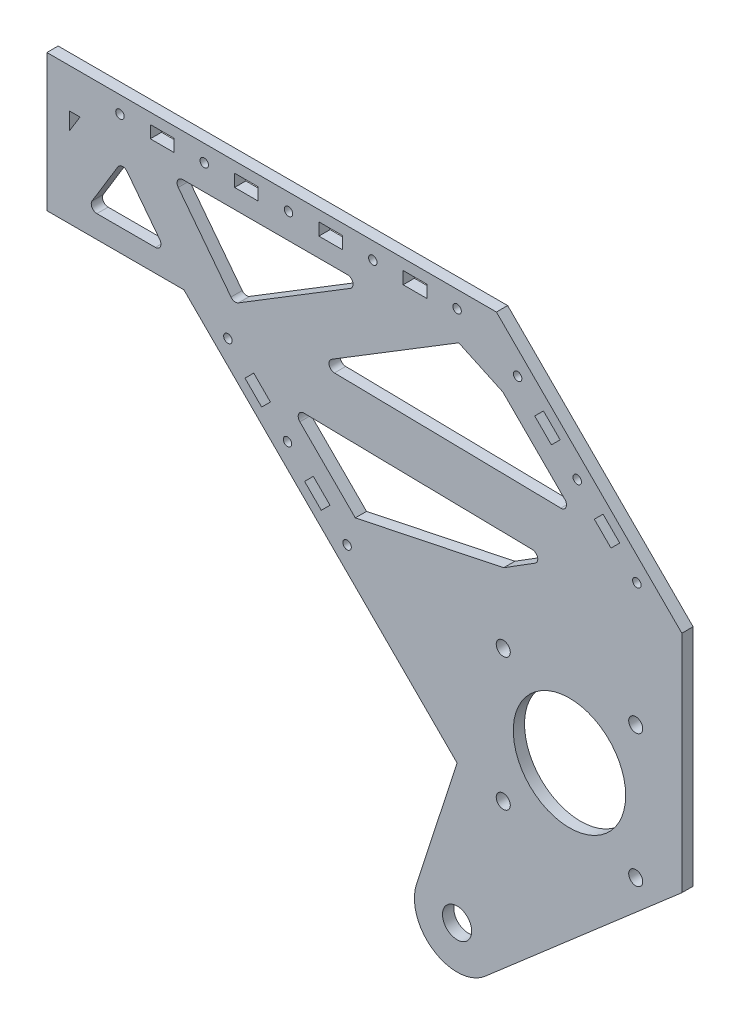
SolidWorks part; units mm, degrees
ref_plane "前视基准面" through (0, 0, 0) normal (0, 0, 1) x (1, 0, 0)
ref_plane "上视基准面" through (0, 0, 0) normal (0, 1, 0) x (1, 0, 0)
ref_plane "右视基准面" through (0, 0, 0) normal (1, 0, 0) x (0, 0, -1)
sketch "草图1" plane through (0, 0, 0) normal (0, 0, 1) x (1, 0, 0)
  line L261 (47.0274, 35.0547) -> (47.0274, 15.0547) construction
  line L316 (-52.9726, 135.0547) -> (-52.9726, 126.7057) construction
  line L332 (-112.9726, 135.0547) -> (-97.9726, 135.0547) construction
  line L334 (-42.1726, 137.2547) -> (-33.7726, 137.2547)
  line L335 (-42.1726, 137.2547) -> (-42.1726, 132.8547)
  line L336 (-42.1726, 132.8547) -> (-33.7726, 132.8547)
  line L337 (-33.7726, 137.2547) -> (-33.7726, 132.8547)
  line L338 (-42.1726, 137.2547) -> (-33.7726, 132.8547) construction
  line L339 (-42.1726, 132.8547) -> (-33.7726, 137.2547) construction
  line L389 (-138.9726, 141.0547) -> (21.0274, 141.0547)
  line L390 (-22.9726, 135.0547) -> (-22.9726, 144.5851) construction
  line L395 (-37.9726, 135.0547) -> (-7.9726, 135.0547) construction
  line L418 (87.0274, 75.0547) -> (21.0274, 141.0547)
  line L419 (-3.7726, 132.8547) -> (-12.1726, 137.2547) construction
  line L420 (-3.7726, 137.2547) -> (-12.1726, 132.8547) construction
  line L421 (7.0274, 135.0547) -> (-7.9726, 135.0547) construction
  line L422 (-12.1726, 137.2547) -> (-12.1726, 132.8547)
  line L423 (-3.7726, 132.8547) -> (-12.1726, 132.8547)
  line L424 (-3.7726, 137.2547) -> (-3.7726, 132.8547)
  line L443 (-3.7726, 137.2547) -> (-12.1726, 137.2547)
  line L444 (-102.1726, 137.2547) -> (-93.7726, 132.8547) construction
  line L445 (-102.1726, 132.8547) -> (-93.7726, 137.2547) construction
  line L446 (7.0274, -4.9453) -> (-138.9726, 141.0547) construction
  line L447 (-67.9726, 135.0547) -> (-97.9726, 135.0547) construction
  line L448 (47.0274, 15.0547) -> (7.0274, -54.2273) construction
  line L449 (-63.7726, 132.8547) -> (-72.1726, 137.2547) construction
  line L483 (-63.7726, 137.2547) -> (-72.1726, 132.8547) construction
  line L515 (47.0274, 35.0547) -> (47.0274, 135.0547) construction
  line L516 (47.0274, 135.0547) -> (-52.9726, 135.0547) construction
  line L517 (-102.1726, 137.2547) -> (-93.7726, 137.2547)
  line L518 (-102.1726, 137.2547) -> (-102.1726, 132.8547)
  line L519 (-102.1726, 132.8547) -> (-93.7726, 132.8547)
  line L520 (-93.7726, 137.2547) -> (-93.7726, 132.8547)
  line L521 (-72.1726, 137.2547) -> (-72.1726, 132.8547)
  line L522 (-63.7726, 132.8547) -> (-72.1726, 132.8547)
  line L523 (-63.7726, 137.2547) -> (-63.7726, 132.8547)
  line L524 (-63.7726, 137.2547) -> (-72.1726, 137.2547)
  line L525 (7.0274, -4.9453) -> (-7.4315, -49.5392)
  line L551 (7.0274, -4.9453) -> (87.0274, -4.9453) construction
  line L552 (7.0274, -4.9453) -> (7.0274, 75.0547) construction
  line L553 (7.0274, 75.0547) -> (87.0274, 75.0547) construction
  line L554 (87.0274, -4.9453) -> (87.0274, 75.0547)
  line L555 (87.0274, -4.9453) -> (16.9882, -65.7087)
  line L556 (21.4033, 132.1936) -> (81.3921, 72.2048) construction
  line L557 (54.0274, 108.0547) -> (35.0674, 89.0947) construction
  line L558 (43.7037, 113.0045) -> (34.6527, 115.8329) construction
  line L559 (55.8659, 94.6197) -> (61.8056, 88.68)
  line L576 (55.8659, 94.6197) -> (58.9772, 97.731)
  line L577 (58.9772, 97.731) -> (64.9169, 91.7913)
  line L578 (61.8056, 88.68) -> (64.9169, 91.7913)
  line L579 (55.8659, 94.6197) -> (64.9169, 91.7913) construction
  line L580 (58.9772, 97.731) -> (61.8056, 88.68) construction
  line L581 (40.5924, 109.8932) -> (37.764, 118.9442) construction
  line L582 (34.6527, 115.8329) -> (37.764, 118.9442)
  line L583 (43.7037, 113.0045) -> (37.764, 118.9442)
  line L584 (40.5924, 109.8932) -> (43.7037, 113.0045)
  line L585 (40.5924, 109.8932) -> (34.6527, 115.8329)
  line L586 (60.3914, 93.2055) -> (58.8358, 91.6499) construction
  line L587 (39.1782, 114.4187) -> (37.6226, 112.8631) construction
  line L588 (-138.9726, 141.0547) -> (-138.9726, 92.2861)
  line L589 (14.0274, 68.0547) -> (9.4285, 72.6537) construction
  line L605 (-25.9726, 28.0547) -> (-21.7299, 32.2974) construction
  line L606 (-138.9726, 92.2861) -> (-90.2039, 92.2861)
  line L607 (-81.7187, 92.2861) -> (-21.7299, 32.2974) construction
  line L608 (-90.2039, 92.2861) -> (7.0274, -4.9453)
  line L609 (-59.4183, 73.097) -> (-68.4693, 75.9255) construction
  line L610 (-47.2561, 54.7123) -> (-41.3164, 48.7726)
  line L611 (-47.2561, 54.7123) -> (-44.1448, 57.8235)
  line L612 (-44.1448, 57.8235) -> (-38.2051, 51.8838)
  line L613 (-41.3164, 48.7726) -> (-38.2051, 51.8838)
  line L614 (-47.2561, 54.7123) -> (-38.2051, 51.8838) construction
  line L615 (-44.1448, 57.8235) -> (-41.3164, 48.7726) construction
  line L616 (-62.5296, 69.9858) -> (-65.358, 79.0367) construction
  line L617 (-68.4693, 75.9255) -> (-65.358, 79.0367)
  line L618 (-59.4183, 73.097) -> (-65.358, 79.0367)
  line L619 (-62.5296, 69.9858) -> (-59.4183, 73.097)
  line L620 (-62.5296, 69.9858) -> (-68.4693, 75.9255)
  line L621 (-42.7306, 53.298) -> (-44.2862, 51.7424) construction
  line L622 (-63.9438, 74.5112) -> (-65.4994, 72.9556) construction
  line L623 (47.0274, 15.0547) -> (89.2922, -52.8694) construction
  line L624 (89.2922, -52.8694) -> (7.0274, -54.2273) construction
  circle A39 centre (-52.9726, 135.0547) radius 1.5
  circle A42 centre (47.0274, 15.0547) radius 20
  circle A49 centre (-22.9726, 135.0547) radius 1.5
  circle A69 centre (7.0274, 135.0547) radius 1.5
  circle A92 centre (-112.9726, 135.0547) radius 1.5
  circle A93 centre (-82.9726, 135.0547) radius 1.5
  circle A94 centre (7.0274, -54.2273) radius 5.2
  circle A96 centre (7.0274, -54.2273) radius 15.2 construction
  arc A97 (-7.4315, -49.5392) -> (16.9882, -65.7087) centre (7.0274, -54.2273) ccw
  circle A98 centre (49.7848, 103.8121) radius 1.5
  circle A99 centre (70.998, 82.5989) radius 1.5
  circle A100 centre (28.5716, 125.0253) radius 1.5
  circle A104 centre (-53.3372, 63.9046) radius 1.5
  circle A105 centre (-32.124, 42.6914) radius 1.5
  circle A106 centre (-74.5504, 85.1178) radius 1.5
  circle A107 centre (70.5974, 38.6247) radius 2.5
  circle A108 centre (70.5974, -8.5153) radius 2.5
  circle A109 centre (23.4574, -8.5153) radius 2.5
  circle A110 centre (23.4574, 38.6247) radius 2.5
  point P5 (210.9534, 218.4629)
  point P6 (288.6284, 218.4629)
  point P54 (-105.4726, 135.0547)
  point P60 (60.3914, 93.2055)
  point P92 (-42.7306, 53.298)
  dimension "D1" = 40
  dimension "D3" = 40
  dimension "D5" = 23.57
  dimension "D4" = 5
  dimension "D6" = 23.57
  dimension "D2" = 40
  dimension "D7" = 60
  dimension "D12" = 3
  dimension "D19" = 10.4
  dimension "D20" = 10
  dimension "D22" = 3
  dimension "D8" = 3
  dimension "D9" = 15
  dimension "D10" = 15
  dimension "D11" = 8.4
  dimension "D13" = 4.4
  dimension "D14" = 6
  dimension "D15" = 45
  dimension "D16" = 15
  dimension "D17" = 8.4
  dimension "D18" = 80
  dimension "D21" = 6
  dimension "D23" = 15
  dimension "D24" = 8.4
  dimension "D25" = 4.4
  dimension "D26" = 4.4
  dimension "D27" = 4
extrude "凸台-拉伸1" add sketch "草图1" along normal blind 4
sketch "草图2" plane through (0, 0, 0) normal (0, 0, -1) x (-1, 0, 0)
  line L0 (74.5504, 85.1178) -> (32.124, 42.6914) construction
  line L3 (-27.0274, 55.0547) -> (-70.998, 82.5989) construction
  line L5 (-7.0274, 135.0547) -> (112.9726, 135.0547) construction
  line L6 (112.9726, 135.0547) -> (138.9726, 92.2861) construction
  line L8 (74.5504, 85.1178) -> (112.9726, 135.0547) construction
  line L9 (138.9726, 92.2861) -> (90.2039, 92.2861) construction
  line L10 (90.2039, 92.2861) -> (74.5504, 85.1178) construction
  line L11 (98.7922, 103.5057) -> (110.419, 118.6169)
  line L12 (113.7131, 118.4362) -> (122.8995, 103.325)
  line L13 (121.1905, 100.2861) -> (100.3774, 100.2861)
  line L14 (52.4384, 75.7338) -> (-40.5172, 74.1251) construction
  line L15 (112.9726, 135.0547) -> (138.9726, 135.0547) construction
  line L16 (138.9726, 141.0547) -> (138.9726, 92.2861) construction
  line L17 (138.9726, 135.0547) -> (138.9726, 92.2861) construction
  line L24 (96.315, 100.2861) -> (112.1978, 120.9288) construction
  line L25 (112.1978, 120.9288) -> (124.7469, 100.2861) construction
  line L26 (127.1982, 127.0547) -> (130.9726, 120.8462)
  line L27 (130.9726, 127.0547) -> (130.9726, 120.8462)
  line L28 (127.1982, 127.0547) -> (130.9726, 127.0547)
  line L29 (74.5504, 85.1178) -> (-7.0274, 135.0547) construction
  line L30 (124.7469, 100.2861) -> (96.315, 100.2861) construction
  line L31 (-23.6122, 63.5354) -> (-40.5172, 74.1251) construction
  line L32 (52.4384, 75.7338) -> (29.2014, 52.4968) construction
  line L33 (-23.3319, 117.5371) -> (-48.886, 91.9829) construction
  line L34 (43.4854, 93.5816) -> (-48.886, 91.9829) construction
  line L35 (43.4854, 93.5816) -> (-7.6073, 124.8574) construction
  line L36 (24.9136, 126.0547) -> (94.6921, 126.0547) construction
  line L37 (72.3501, 97.0171) -> (24.9136, 126.0547) construction
  line L38 (73.4463, 98.4417) -> (92.2149, 122.8351)
  line L39 (32.0116, 126.0547) -> (90.6298, 126.0547)
  line L40 (70.817, 97.9555) -> (30.9675, 122.349)
  line L41 (74.5504, 85.1178) -> (-70.998, 82.5989) construction
  line L42 (-7.0274, 135.0547) -> (-28.5716, 125.0253) construction
  line L43 (-28.5716, 125.0253) -> (-70.998, 82.5989) construction
  line L44 (36.6167, 93.4627) -> (-43.9377, 92.0686)
  line L45 (-23.3319, 117.5371) -> (-45.3865, 95.4825)
  line L46 (-7.6073, 124.8574) -> (-23.3319, 117.5371)
  line L47 (37.6263, 97.1682) -> (-7.6073, 124.8574)
  line L48 (32.124, 42.6914) -> (-27.0274, 55.0547) construction
  line L49 (29.2014, 52.4968) -> (-23.6122, 63.5354)
  line L50 (-23.6122, 63.5354) -> (-34.8054, 70.5471)
  line L51 (47.4901, 75.6482) -> (-33.7783, 74.2417)
  line L52 (48.9389, 72.2343) -> (29.2014, 52.4968)
  line L53 (96.315, 100.2861) -> (96.315, 100.2861) construction
  line L54 (72.3501, 97.0171) -> (94.6921, 126.0547) construction
  arc A2 (110.419, 118.6169) -> (113.7131, 118.4362) centre (112.0041, 117.3973) cw
  arc A3 (98.7922, 103.5057) -> (100.3774, 100.2861) centre (100.3774, 102.2861) ccw
  arc A4 (121.1905, 100.2861) -> (122.8995, 103.325) centre (121.1905, 102.2861) ccw
  arc A6 (-33.7783, 74.2417) -> (-34.8054, 70.5471) centre (-33.7437, 72.242) ccw
  arc A7 (47.4901, 75.6482) -> (48.9389, 72.2343) centre (47.5247, 73.6485) cw
  arc A8 (-45.3865, 95.4825) -> (-43.9377, 92.0686) centre (-43.9723, 94.0683) ccw
  arc A9 (36.6167, 93.4627) -> (37.6263, 97.1682) centre (36.5821, 95.4624) ccw
  arc A10 (32.0116, 126.0547) -> (30.9675, 122.349) centre (32.0116, 124.0547) ccw
  arc A11 (90.6298, 126.0547) -> (92.2149, 122.8351) centre (90.6298, 124.0547) cw
  arc A12 (70.817, 97.9555) -> (73.4463, 98.4417) centre (71.8612, 99.6613) ccw
  dimension "D1" = 8
  dimension "D2" = 8
  dimension "D3" = 9
  dimension "D4" = 9
  dimension "D5" = 9
extrude "切除-拉伸1" cut sketch "草图2" against normal blind 10
